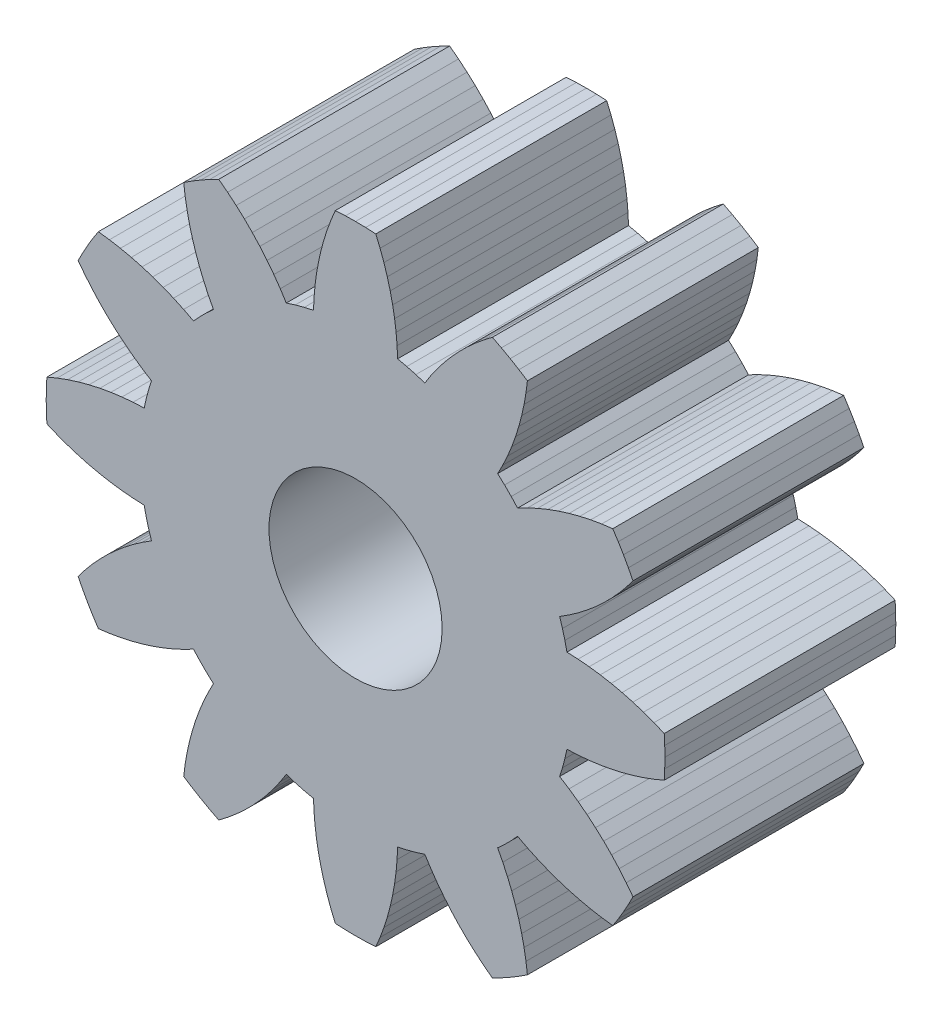
SolidWorks part; units mm, degrees
ref_plane "Front Plane" through (0, 0, 0) normal (0, 0, 1) x (1, 0, 0)
ref_plane "Top Plane" through (0, 0, 0) normal (0, 1, 0) x (1, 0, 0)
ref_plane "Right Plane" through (0, 0, 0) normal (1, 0, 0) x (0, 0, -1)
sketch "Sketch1" plane through (0, 0, 0) normal (0, 0, 1) x (1, 0, 0)
  line L25 (-0.7284, -3.6618) -> (-0.7195, -3.8547)
  line L26 (-0.7195, -3.8547) -> (-0.7021, -4.0471)
  line L27 (-0.7021, -4.0471) -> (-0.6765, -4.2386)
  line L28 (-0.6765, -4.2386) -> (-0.6425, -4.4287)
  line L29 (-0.6425, -4.4287) -> (-0.6002, -4.6172)
  line L30 (-0.6002, -4.6172) -> (-0.5498, -4.8037)
  line L31 (-0.5498, -4.8037) -> (-0.4913, -4.9878)
  line L32 (-0.4913, -4.9878) -> (-0.4248, -5.1692)
  line L33 (-0.4248, -5.1692) -> (-0.3505, -5.3475)
  line L34 (-0.3505, -5.3475) -> (-0.1753, -5.3561)
  line L35 (-0.1753, -5.3561) -> (0, -5.359)
  line L36 (0, -5.359) -> (0.1753, -5.3561)
  line L37 (0.1753, -5.3561) -> (0.3505, -5.3475)
  line L38 (0.3505, -5.3475) -> (0.4248, -5.1692)
  line L39 (0.4248, -5.1692) -> (0.4913, -4.9878)
  line L40 (0.4913, -4.9878) -> (0.5498, -4.8037)
  line L41 (0.5498, -4.8037) -> (0.6002, -4.6172)
  line L42 (0.6002, -4.6172) -> (0.6425, -4.4287)
  line L43 (0.6425, -4.4287) -> (0.6765, -4.2386)
  line L44 (0.6765, -4.2386) -> (0.7021, -4.0471)
  line L45 (0.7021, -4.0471) -> (0.7195, -3.8547)
  line L46 (0.7195, -3.8547) -> (0.7284, -3.6618)
  line L47 (0.7284, -3.6618) -> (0.8874, -3.6265)
  line L48 (0.8874, -3.6265) -> (1.0447, -3.5844)
  line L49 (1.0447, -3.5844) -> (1.2001, -3.5354)
  line L50 (-2.4617, -2.807) -> (-2.5504, -2.9786)
  line L51 (-2.5504, -2.9786) -> (-2.6316, -3.1538)
  line L52 (-2.6316, -3.1538) -> (-2.7051, -3.3325)
  line L53 (-2.7051, -3.3325) -> (-2.7708, -3.5142)
  line L54 (-2.7708, -3.5142) -> (-2.8284, -3.6985)
  line L55 (-2.8284, -3.6985) -> (-2.878, -3.8853)
  line L56 (-2.878, -3.8853) -> (-2.9194, -4.0739)
  line L57 (-2.9194, -4.0739) -> (-2.9525, -4.2642)
  line L58 (-2.9525, -4.2642) -> (-2.9773, -4.4558)
  line L59 (-2.9773, -4.4558) -> (-2.8299, -4.5509)
  line L60 (-2.8299, -4.5509) -> (-2.6795, -4.641)
  line L61 (-2.6795, -4.641) -> (-2.5262, -4.7262)
  line L62 (-2.5262, -4.7262) -> (-2.3702, -4.8063)
  line L63 (-2.3702, -4.8063) -> (-2.2167, -4.6891)
  line L64 (-2.2167, -4.6891) -> (-2.0685, -4.5652)
  line L65 (-2.0685, -4.5652) -> (-1.9257, -4.435)
  line L66 (-1.9257, -4.435) -> (-1.7888, -4.2988)
  line L67 (-1.7888, -4.2988) -> (-1.658, -4.1566)
  line L68 (-1.658, -4.1566) -> (-1.5335, -4.009)
  line L69 (-1.5335, -4.009) -> (-1.4155, -3.856)
  line L70 (-1.4155, -3.856) -> (-1.3043, -3.698)
  line L71 (-1.3043, -3.698) -> (-1.2001, -3.5354)
  line L72 (-1.2001, -3.5354) -> (-1.0447, -3.5844)
  line L73 (-1.0447, -3.5844) -> (-0.8874, -3.6265)
  line L74 (-0.8874, -3.6265) -> (-0.7284, -3.6618)
  line L75 (-3.5354, -1.2001) -> (-3.698, -1.3043)
  line L76 (-3.698, -1.3043) -> (-3.856, -1.4155)
  line L77 (-3.856, -1.4155) -> (-4.009, -1.5335)
  line L78 (-4.009, -1.5335) -> (-4.1566, -1.658)
  line L79 (-4.1566, -1.658) -> (-4.2988, -1.7888)
  line L80 (-4.2988, -1.7888) -> (-4.435, -1.9257)
  line L81 (-4.435, -1.9257) -> (-4.5652, -2.0685)
  line L82 (-4.5652, -2.0685) -> (-4.6891, -2.2167)
  line L83 (-4.6891, -2.2167) -> (-4.8063, -2.3702)
  line L84 (-4.8063, -2.3702) -> (-4.7262, -2.5262)
  line L85 (-4.7262, -2.5262) -> (-4.641, -2.6795)
  line L86 (-4.641, -2.6795) -> (-4.5509, -2.8299)
  line L87 (-4.5509, -2.8299) -> (-4.4558, -2.9773)
  line L88 (-4.4558, -2.9773) -> (-4.2642, -2.9525)
  line L89 (-4.2642, -2.9525) -> (-4.0739, -2.9194)
  line L90 (-4.0739, -2.9194) -> (-3.8853, -2.878)
  line L91 (-3.8853, -2.878) -> (-3.6985, -2.8284)
  line L92 (-3.6985, -2.8284) -> (-3.5142, -2.7708)
  line L93 (-3.5142, -2.7708) -> (-3.3325, -2.7051)
  line L94 (-3.3325, -2.7051) -> (-3.1538, -2.6316)
  line L95 (-3.1538, -2.6316) -> (-2.9786, -2.5504)
  line L96 (-2.9786, -2.5504) -> (-2.807, -2.4617)
  line L97 (-2.807, -2.4617) -> (-2.697, -2.5818)
  line L98 (-2.697, -2.5818) -> (-2.5818, -2.697)
  line L99 (-2.5818, -2.697) -> (-2.4617, -2.807)
  line L100 (-3.6618, 0.7284) -> (-3.8547, 0.7195)
  line L101 (-3.8547, 0.7195) -> (-4.0471, 0.7021)
  line L102 (-4.0471, 0.7021) -> (-4.2386, 0.6765)
  line L103 (-4.2386, 0.6765) -> (-4.4287, 0.6425)
  line L104 (-4.4287, 0.6425) -> (-4.6172, 0.6002)
  line L105 (-4.6172, 0.6002) -> (-4.8037, 0.5498)
  line L106 (-4.8037, 0.5498) -> (-4.9878, 0.4913)
  line L107 (-4.9878, 0.4913) -> (-5.1692, 0.4248)
  line L108 (-5.1692, 0.4248) -> (-5.3475, 0.3505)
  line L109 (-5.3475, 0.3505) -> (-5.3561, 0.1753)
  line L110 (-5.3561, 0.1753) -> (-5.359, 0)
  line L111 (-5.359, 0) -> (-5.3561, -0.1753)
  line L112 (-5.3561, -0.1753) -> (-5.3475, -0.3505)
  line L113 (-5.3475, -0.3505) -> (-5.1692, -0.4248)
  line L114 (-5.1692, -0.4248) -> (-4.9878, -0.4913)
  line L115 (-4.9878, -0.4913) -> (-4.8037, -0.5498)
  line L116 (-4.8037, -0.5498) -> (-4.6172, -0.6002)
  line L117 (-4.6172, -0.6002) -> (-4.4287, -0.6425)
  line L118 (-4.4287, -0.6425) -> (-4.2386, -0.6765)
  line L119 (-4.2386, -0.6765) -> (-4.0471, -0.7021)
  line L120 (-4.0471, -0.7021) -> (-3.8547, -0.7195)
  line L121 (-3.8547, -0.7195) -> (-3.6618, -0.7284)
  line L122 (-3.6618, -0.7284) -> (-3.6265, -0.8874)
  line L123 (-3.6265, -0.8874) -> (-3.5844, -1.0447)
  line L124 (-3.5844, -1.0447) -> (-3.5354, -1.2001)
  line L125 (-2.807, 2.4617) -> (-2.9786, 2.5504)
  line L126 (-2.9786, 2.5504) -> (-3.1538, 2.6316)
  line L127 (-3.1538, 2.6316) -> (-3.3325, 2.7051)
  line L128 (-3.3325, 2.7051) -> (-3.5142, 2.7708)
  line L129 (-3.5142, 2.7708) -> (-3.6985, 2.8284)
  line L130 (-3.6985, 2.8284) -> (-3.8853, 2.878)
  line L131 (-3.8853, 2.878) -> (-4.0739, 2.9194)
  line L132 (-4.0739, 2.9194) -> (-4.2642, 2.9525)
  line L133 (-4.2642, 2.9525) -> (-4.4558, 2.9773)
  line L134 (-4.4558, 2.9773) -> (-4.5509, 2.8299)
  line L135 (-4.5509, 2.8299) -> (-4.641, 2.6795)
  line L136 (-4.641, 2.6795) -> (-4.7262, 2.5262)
  line L137 (-4.7262, 2.5262) -> (-4.8063, 2.3702)
  line L138 (-4.8063, 2.3702) -> (-4.6891, 2.2167)
  line L139 (-4.6891, 2.2167) -> (-4.5652, 2.0685)
  line L140 (-4.5652, 2.0685) -> (-4.435, 1.9257)
  line L141 (-4.435, 1.9257) -> (-4.2988, 1.7888)
  line L142 (-4.2988, 1.7888) -> (-4.1566, 1.658)
  line L143 (-4.1566, 1.658) -> (-4.009, 1.5335)
  line L144 (-4.009, 1.5335) -> (-3.856, 1.4155)
  line L145 (-3.856, 1.4155) -> (-3.698, 1.3043)
  line L146 (-3.698, 1.3043) -> (-3.5354, 1.2001)
  line L147 (-3.5354, 1.2001) -> (-3.5844, 1.0447)
  line L148 (-3.5844, 1.0447) -> (-3.6265, 0.8874)
  line L149 (-3.6265, 0.8874) -> (-3.6618, 0.7284)
  line L150 (-1.2001, 3.5354) -> (-1.3043, 3.698)
  line L151 (-1.3043, 3.698) -> (-1.4155, 3.856)
  line L152 (-1.4155, 3.856) -> (-1.5335, 4.009)
  line L153 (-1.5335, 4.009) -> (-1.658, 4.1566)
  line L154 (-1.658, 4.1566) -> (-1.7888, 4.2988)
  line L155 (-1.7888, 4.2988) -> (-1.9257, 4.435)
  line L156 (-1.9257, 4.435) -> (-2.0685, 4.5652)
  line L157 (-2.0685, 4.5652) -> (-2.2167, 4.6891)
  line L158 (-2.2167, 4.6891) -> (-2.3702, 4.8063)
  line L159 (-2.3702, 4.8063) -> (-2.5262, 4.7262)
  line L160 (-2.5262, 4.7262) -> (-2.6795, 4.641)
  line L161 (-2.6795, 4.641) -> (-2.8299, 4.5509)
  line L162 (-2.8299, 4.5509) -> (-2.9773, 4.4558)
  line L163 (-2.9773, 4.4558) -> (-2.9525, 4.2642)
  line L164 (-2.9525, 4.2642) -> (-2.9194, 4.0739)
  line L165 (-2.9194, 4.0739) -> (-2.878, 3.8853)
  line L166 (-2.878, 3.8853) -> (-2.8284, 3.6985)
  line L167 (-2.8284, 3.6985) -> (-2.7708, 3.5142)
  line L168 (-2.7708, 3.5142) -> (-2.7051, 3.3325)
  line L169 (-2.7051, 3.3325) -> (-2.6316, 3.1538)
  line L170 (-2.6316, 3.1538) -> (-2.5504, 2.9786)
  line L171 (-2.5504, 2.9786) -> (-2.4617, 2.807)
  line L172 (-2.4617, 2.807) -> (-2.5818, 2.697)
  line L173 (-2.5818, 2.697) -> (-2.697, 2.5818)
  line L174 (-2.697, 2.5818) -> (-2.807, 2.4617)
  line L175 (0.7284, 3.6618) -> (0.7195, 3.8547)
  line L176 (0.7195, 3.8547) -> (0.7021, 4.0471)
  line L177 (0.7021, 4.0471) -> (0.6765, 4.2386)
  line L178 (0.6765, 4.2386) -> (0.6425, 4.4287)
  line L179 (0.6425, 4.4287) -> (0.6002, 4.6172)
  line L180 (0.6002, 4.6172) -> (0.5498, 4.8037)
  line L181 (0.5498, 4.8037) -> (0.4913, 4.9878)
  line L182 (0.4913, 4.9878) -> (0.4248, 5.1692)
  line L183 (0.4248, 5.1692) -> (0.3505, 5.3475)
  line L184 (0.3505, 5.3475) -> (0.1753, 5.3561)
  line L185 (0.1753, 5.3561) -> (0, 5.359)
  line L186 (0, 5.359) -> (-0.1753, 5.3561)
  line L187 (-0.1753, 5.3561) -> (-0.3505, 5.3475)
  line L188 (-0.3505, 5.3475) -> (-0.4248, 5.1692)
  line L189 (-0.4248, 5.1692) -> (-0.4913, 4.9878)
  line L190 (-0.4913, 4.9878) -> (-0.5498, 4.8037)
  line L191 (-0.5498, 4.8037) -> (-0.6002, 4.6172)
  line L192 (-0.6002, 4.6172) -> (-0.6425, 4.4287)
  line L193 (-0.6425, 4.4287) -> (-0.6765, 4.2386)
  line L194 (-0.6765, 4.2386) -> (-0.7021, 4.0471)
  line L195 (-0.7021, 4.0471) -> (-0.7195, 3.8547)
  line L196 (-0.7195, 3.8547) -> (-0.7284, 3.6618)
  line L197 (-0.7284, 3.6618) -> (-0.8874, 3.6265)
  line L198 (-0.8874, 3.6265) -> (-1.0447, 3.5844)
  line L199 (-1.0447, 3.5844) -> (-1.2001, 3.5354)
  line L200 (2.4617, 2.807) -> (2.5504, 2.9786)
  line L201 (2.5504, 2.9786) -> (2.6316, 3.1538)
  line L202 (2.6316, 3.1538) -> (2.7051, 3.3325)
  line L203 (2.7051, 3.3325) -> (2.7708, 3.5142)
  line L204 (2.7708, 3.5142) -> (2.8284, 3.6985)
  line L205 (2.8284, 3.6985) -> (2.878, 3.8853)
  line L206 (2.878, 3.8853) -> (2.9194, 4.0739)
  line L207 (2.9194, 4.0739) -> (2.9525, 4.2642)
  line L208 (2.9525, 4.2642) -> (2.9773, 4.4558)
  line L209 (2.9773, 4.4558) -> (2.8299, 4.5509)
  line L210 (2.8299, 4.5509) -> (2.6795, 4.641)
  line L211 (2.6795, 4.641) -> (2.5262, 4.7262)
  line L212 (2.5262, 4.7262) -> (2.3702, 4.8063)
  line L213 (2.3702, 4.8063) -> (2.2167, 4.6891)
  line L214 (2.2167, 4.6891) -> (2.0685, 4.5652)
  line L215 (2.0685, 4.5652) -> (1.9257, 4.435)
  line L216 (1.9257, 4.435) -> (1.7888, 4.2988)
  line L217 (1.7888, 4.2988) -> (1.658, 4.1566)
  line L218 (1.658, 4.1566) -> (1.5335, 4.009)
  line L219 (1.5335, 4.009) -> (1.4155, 3.856)
  line L220 (1.4155, 3.856) -> (1.3043, 3.698)
  line L221 (1.3043, 3.698) -> (1.2001, 3.5354)
  line L222 (1.2001, 3.5354) -> (1.0447, 3.5844)
  line L223 (1.0447, 3.5844) -> (0.8874, 3.6265)
  line L224 (0.8874, 3.6265) -> (0.7284, 3.6618)
  line L225 (3.5354, 1.2001) -> (3.698, 1.3043)
  line L226 (3.698, 1.3043) -> (3.856, 1.4155)
  line L227 (3.856, 1.4155) -> (4.009, 1.5335)
  line L228 (4.009, 1.5335) -> (4.1566, 1.658)
  line L229 (4.1566, 1.658) -> (4.2988, 1.7888)
  line L230 (4.2988, 1.7888) -> (4.435, 1.9257)
  line L231 (4.435, 1.9257) -> (4.5652, 2.0685)
  line L232 (4.5652, 2.0685) -> (4.6891, 2.2167)
  line L233 (4.6891, 2.2167) -> (4.8063, 2.3702)
  line L234 (4.8063, 2.3702) -> (4.7262, 2.5262)
  line L235 (4.7262, 2.5262) -> (4.641, 2.6795)
  line L236 (4.641, 2.6795) -> (4.5509, 2.8299)
  line L237 (4.5509, 2.8299) -> (4.4558, 2.9773)
  line L238 (4.4558, 2.9773) -> (4.2642, 2.9525)
  line L239 (4.2642, 2.9525) -> (4.0739, 2.9194)
  line L240 (4.0739, 2.9194) -> (3.8853, 2.878)
  line L241 (3.8853, 2.878) -> (3.6985, 2.8284)
  line L242 (3.6985, 2.8284) -> (3.5142, 2.7708)
  line L243 (3.5142, 2.7708) -> (3.3325, 2.7051)
  line L244 (3.3325, 2.7051) -> (3.1538, 2.6316)
  line L245 (3.1538, 2.6316) -> (2.9786, 2.5504)
  line L246 (2.9786, 2.5504) -> (2.807, 2.4617)
  line L247 (2.807, 2.4617) -> (2.697, 2.5818)
  line L248 (2.697, 2.5818) -> (2.5818, 2.697)
  line L249 (2.5818, 2.697) -> (2.4617, 2.807)
  line L250 (3.6618, -0.7284) -> (3.8547, -0.7195)
  line L251 (3.8547, -0.7195) -> (4.0471, -0.7021)
  line L252 (4.0471, -0.7021) -> (4.2386, -0.6765)
  line L253 (4.2386, -0.6765) -> (4.4287, -0.6425)
  line L254 (4.4287, -0.6425) -> (4.6172, -0.6002)
  line L255 (4.6172, -0.6002) -> (4.8037, -0.5498)
  line L256 (4.8037, -0.5498) -> (4.9878, -0.4913)
  line L257 (4.9878, -0.4913) -> (5.1692, -0.4248)
  line L258 (5.1692, -0.4248) -> (5.3475, -0.3505)
  line L259 (5.3475, -0.3505) -> (5.3561, -0.1753)
  line L260 (5.3561, -0.1753) -> (5.359, 0)
  line L261 (5.359, 0) -> (5.3561, 0.1753)
  line L262 (5.3561, 0.1753) -> (5.3475, 0.3505)
  line L263 (5.3475, 0.3505) -> (5.1692, 0.4248)
  line L264 (5.1692, 0.4248) -> (4.9878, 0.4913)
  line L265 (4.9878, 0.4913) -> (4.8037, 0.5498)
  line L266 (4.8037, 0.5498) -> (4.6172, 0.6002)
  line L267 (4.6172, 0.6002) -> (4.4287, 0.6425)
  line L268 (4.4287, 0.6425) -> (4.2386, 0.6765)
  line L269 (4.2386, 0.6765) -> (4.0471, 0.7021)
  line L270 (4.0471, 0.7021) -> (3.8547, 0.7195)
  line L271 (3.8547, 0.7195) -> (3.6618, 0.7284)
  line L272 (3.6618, 0.7284) -> (3.6265, 0.8874)
  line L273 (3.6265, 0.8874) -> (3.5844, 1.0447)
  line L274 (3.5844, 1.0447) -> (3.5354, 1.2001)
  line L275 (2.807, -2.4617) -> (2.9786, -2.5504)
  line L276 (2.9786, -2.5504) -> (3.1538, -2.6316)
  line L277 (3.1538, -2.6316) -> (3.3325, -2.7051)
  line L278 (3.3325, -2.7051) -> (3.5142, -2.7708)
  line L279 (3.5142, -2.7708) -> (3.6985, -2.8284)
  line L280 (3.6985, -2.8284) -> (3.8853, -2.878)
  line L281 (3.8853, -2.878) -> (4.0739, -2.9194)
  line L282 (4.0739, -2.9194) -> (4.2642, -2.9525)
  line L283 (4.2642, -2.9525) -> (4.4558, -2.9773)
  line L284 (4.4558, -2.9773) -> (4.5509, -2.8299)
  line L285 (4.5509, -2.8299) -> (4.641, -2.6795)
  line L286 (4.641, -2.6795) -> (4.7262, -2.5262)
  line L287 (4.7262, -2.5262) -> (4.8063, -2.3702)
  line L288 (4.8063, -2.3702) -> (4.6891, -2.2167)
  line L289 (4.6891, -2.2167) -> (4.5652, -2.0685)
  line L290 (4.5652, -2.0685) -> (4.435, -1.9257)
  line L291 (4.435, -1.9257) -> (4.2988, -1.7888)
  line L292 (4.2988, -1.7888) -> (4.1566, -1.658)
  line L293 (4.1566, -1.658) -> (4.009, -1.5335)
  line L294 (4.009, -1.5335) -> (3.856, -1.4155)
  line L295 (3.856, -1.4155) -> (3.698, -1.3043)
  line L296 (3.698, -1.3043) -> (3.5354, -1.2001)
  line L297 (3.5354, -1.2001) -> (3.5844, -1.0447)
  line L298 (3.5844, -1.0447) -> (3.6265, -0.8874)
  line L299 (3.6265, -0.8874) -> (3.6618, -0.7284)
  line L300 (1.2001, -3.5354) -> (1.3043, -3.698)
  line L301 (1.3043, -3.698) -> (1.4155, -3.856)
  line L302 (1.4155, -3.856) -> (1.5335, -4.009)
  line L303 (1.5335, -4.009) -> (1.658, -4.1566)
  line L304 (1.658, -4.1566) -> (1.7888, -4.2988)
  line L305 (1.7888, -4.2988) -> (1.9257, -4.435)
  line L306 (1.9257, -4.435) -> (2.0685, -4.5652)
  line L307 (2.0685, -4.5652) -> (2.2167, -4.6891)
  line L308 (2.2167, -4.6891) -> (2.3702, -4.8063)
  line L309 (2.3702, -4.8063) -> (2.5262, -4.7262)
  line L310 (2.5262, -4.7262) -> (2.6795, -4.641)
  line L311 (2.6795, -4.641) -> (2.8299, -4.5509)
  line L312 (2.8299, -4.5509) -> (2.9773, -4.4558)
  line L313 (2.9773, -4.4558) -> (2.9525, -4.2642)
  line L314 (2.9525, -4.2642) -> (2.9194, -4.0739)
  line L315 (2.9194, -4.0739) -> (2.878, -3.8853)
  line L316 (2.878, -3.8853) -> (2.8284, -3.6985)
  line L317 (2.8284, -3.6985) -> (2.7708, -3.5142)
  line L318 (2.7708, -3.5142) -> (2.7051, -3.3325)
  line L319 (2.7051, -3.3325) -> (2.6316, -3.1538)
  line L320 (2.6316, -3.1538) -> (2.5504, -2.9786)
  line L321 (2.5504, -2.9786) -> (2.4617, -2.807)
  line L322 (2.4617, -2.807) -> (2.5818, -2.697)
  line L323 (2.5818, -2.697) -> (2.697, -2.5818)
  line L324 (2.697, -2.5818) -> (2.807, -2.4617)
  circle A0 centre (0, 0) radius 3.7335 construction
  point P320 (0, 0)
  dimension "D1" = 12
extrude "Boss-Extrude1" add sketch "Sketch1" along normal blind 4
sketch "Sketch2" plane through (0, 0, 4) normal (0, 0, 1) x (1, 0, 0)
  circle A0 centre (0, 0) radius 1.5
  dimension "D1" = 3
extrude "Cut-Extrude1" cut sketch "Sketch2" against normal up to next
